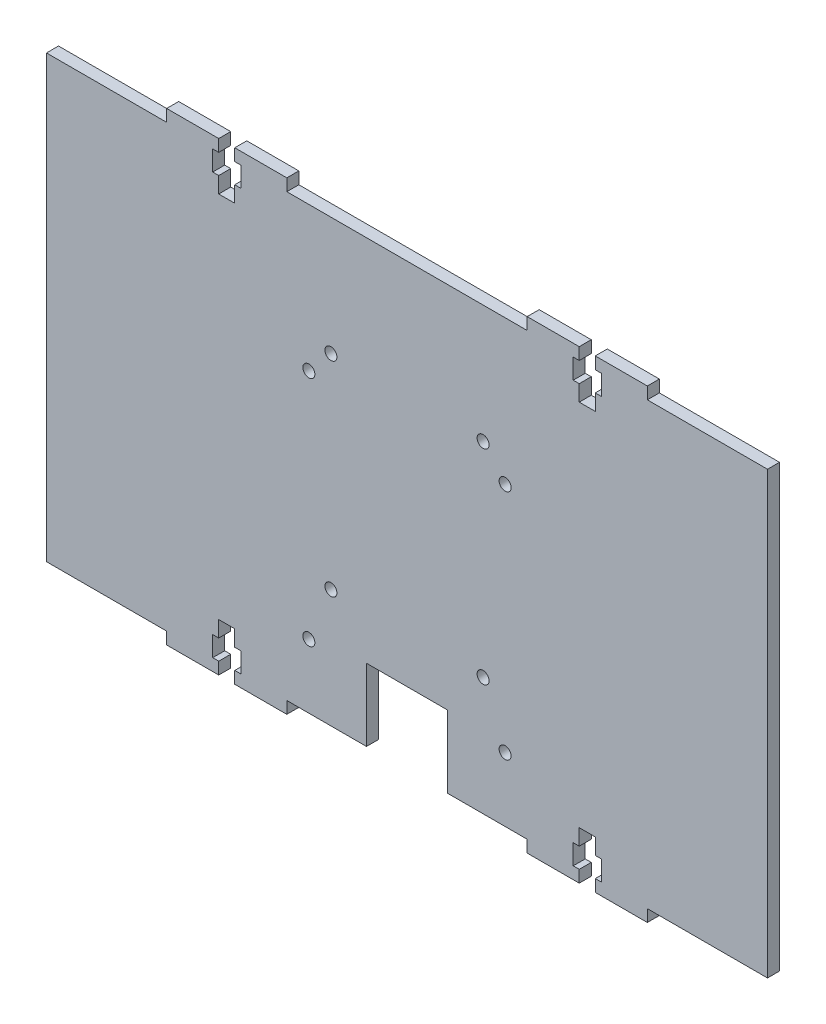
SolidWorks part; units mm, degrees
ref_plane "前视基准面" through (0, 0, 0) normal (0, 0, 1) x (1, 0, 0)
ref_plane "上视基准面" through (0, 0, 0) normal (0, 1, 0) x (1, 0, 0)
ref_plane "右视基准面" through (0, 0, 0) normal (1, 0, 0) x (0, 0, -1)
sketch "草图1" plane through (0, 0, 0) normal (0, 0, 1) x (1, 0, 0)
  line L0 (90, 0) -> (90, -110)
  line L1 (0, 0) -> (180, 0)
  line L2 (0, 0) -> (0, -110)
  line L3 (0, -110) -> (180, -110)
  line L4 (180, 0) -> (180, -110)
  line L5 (0, -55) -> (180, -55)
  line L6 (137, -9) -> (133, -9)
  line L7 (30, 0) -> (60, 0)
  line L8 (30, 0) -> (30, 3)
  line L9 (30, 3) -> (60, 3)
  line L10 (60, 0) -> (60, 3)
  line L11 (43, 3) -> (47, 3)
  line L12 (43, 3) -> (43, -9)
  line L13 (43, -9) -> (47, -9)
  line L14 (47, 3) -> (47, -9)
  line L15 (41.5, 0) -> (48.5, 0)
  line L16 (41.5, 0) -> (41.5, -5)
  line L17 (41.5, -5) -> (48.5, -5)
  line L18 (48.5, 0) -> (48.5, -5)
  line L19 (133, 3) -> (133, -9)
  line L20 (137, 3) -> (133, 3)
  line L21 (137, 3) -> (137, -9)
  line L22 (138.5, -5) -> (131.5, -5)
  line L23 (131.5, 0) -> (131.5, -5)
  line L24 (138.5, 0) -> (131.5, 0)
  line L25 (138.5, 0) -> (138.5, -5)
  line L26 (150, 3) -> (120, 3)
  line L27 (120, 0) -> (120, 3)
  line L28 (150, 0) -> (120, 0)
  line L29 (150, 0) -> (150, 3)
  line L30 (30, -113) -> (60, -113)
  line L31 (60, -110) -> (60, -113)
  line L32 (30, -110) -> (60, -110)
  line L33 (30, -110) -> (30, -113)
  line L34 (41.5, -105) -> (48.5, -105)
  line L35 (48.5, -110) -> (48.5, -105)
  line L36 (41.5, -110) -> (48.5, -110)
  line L37 (41.5, -110) -> (41.5, -105)
  line L38 (43, -101) -> (47, -101)
  line L39 (47, -113) -> (47, -101)
  line L40 (43, -113) -> (47, -113)
  line L41 (43, -113) -> (43, -101)
  line L42 (138.5, -110) -> (138.5, -105)
  line L43 (138.5, -110) -> (131.5, -110)
  line L44 (131.5, -110) -> (131.5, -105)
  line L45 (138.5, -105) -> (131.5, -105)
  line L46 (137, -113) -> (137, -101)
  line L47 (137, -113) -> (133, -113)
  line L48 (133, -113) -> (133, -101)
  line L49 (137, -101) -> (133, -101)
  line L50 (150, -110) -> (150, -113)
  line L51 (150, -110) -> (120, -110)
  line L52 (120, -110) -> (120, -113)
  line L53 (150, -113) -> (120, -113)
  line L55 (62, -12.5) -> (118, -12.5)
  line L56 (62, -12.5) -> (62, -97.5)
  line L57 (62, -97.5) -> (118, -97.5)
  line L58 (118, -12.5) -> (118, -97.5)
  line L59 (62, -12.5) -> (118, -97.5) construction
  line L60 (62, -97.5) -> (118, -12.5) construction
  circle A0 centre (65.5, -94) radius 1.5
  circle A1 centre (65.5, -36) radius 1.5
  circle A2 centre (114.5, -94) radius 1.5
  circle A3 centre (114.5, -36) radius 1.5
  point P57 (90, -55)
  dimension "D14" = 3
  dimension "D15" = 3.5
  dimension "D16" = 3.5
  dimension "D1" = 180
  dimension "D2" = 110
  dimension "D3" = 30
  dimension "D4" = 3
  dimension "D5" = 30
  dimension "D6" = 4
  dimension "D7" = 13
  dimension "D8" = 12
  dimension "D9" = 7
  dimension "D10" = 5
  dimension "D11" = 1.5
  dimension "D12" = 56
  dimension "D13" = 85
  dimension "D17" = 2
extrude "凸台-拉伸1" add sketch "草图1" along normal blind 3 contours L12 L9 L8 L1 L7 | L9 L14 L1 L7 L10 | L27 L1 L19 L26 | L1 L29 L26 L21 | L55 L58 L5 L4 L1 L25 L22 L21 L6 L19 L23 L0 | L56 L55 L0 L1 L7 L18 L17 L14 L13 L12 L16 L2 L5 | L55 L56 L5 L0 A1 | L58 L55 L0 L5 A3 | L30 L41 L32 L3 L33 | L39 L30 L31 L32 L36 | L53 L48 L3 L52 | L53 L50 L3 L43 L46 | L5 L58 L57 L0 L3 L44 L45 L48 L49 L46 L42 L4 | L57 L56 L5 L2 L3 L37 L34 L41 L38 L39 L35 L32 L0 | L56 L57 L0 L5 A0 | L58 L5 L0 L57 A2
sketch "Sketch1" plane through (0, 0, 3) normal (0, 0, 1) x (1, 0, 0)
  line L3 (60, -110) -> (120, -110) construction
  line L4 (79.8862, -92) -> (100.1138, -92)
  line L5 (79.8862, -92) -> (79.8862, -110)
  line L6 (79.8862, -110) -> (100.1138, -110)
  line L7 (100.1138, -92) -> (100.1138, -110)
  line L8 (90, -110) -> (90, -92) construction
  line L9 (79.8862, -101) -> (100.1138, -101) construction
  point P6 (90, -101)
extrude "Cut-Extrude1" cut sketch "Sketch1" against normal blind 10 contours L5 L4 L7 L6
sketch "草图2" plane through (0, 0, 3) normal (0, 0, 1) x (1, 0, 0)
  line L0 (0, -55) -> (180, -55)
  line L1 (0, 0) -> (0, -110) construction
  line L2 (180, 0) -> (180, -110) construction
  line L3 (90, 0) -> (90, -92)
  line L4 (60, 0) -> (120, 0) construction
  line L5 (79.8862, -92) -> (100.1138, -92) construction
  line L7 (71, -29.5) -> (109, -29.5)
  line L8 (71, -29.5) -> (71, -80.5)
  line L9 (71, -80.5) -> (109, -80.5)
  line L10 (109, -29.5) -> (109, -80.5)
  line L11 (71, -29.5) -> (109, -80.5) construction
  line L12 (71, -80.5) -> (109, -29.5) construction
  circle A1 centre (109, -80.5) radius 1.5
  circle A2 centre (109, -29.5) radius 1.5
  circle A3 centre (71, -80.5) radius 1.5
  circle A4 centre (71, -29.5) radius 1.5
  point P12 (90, -55)
  dimension "D3" = 3
  dimension "D1" = 38
  dimension "D2" = 51
extrude "切除-拉伸1" cut sketch "草图2" against normal through all contours L7 A4 L8 | A2 L7 L10 | A2 L10 L7 | L8 A4 L7 | A3 L9 L8 | A3 L8 L9 | L9 A1 L10 | L10 A1 L9
